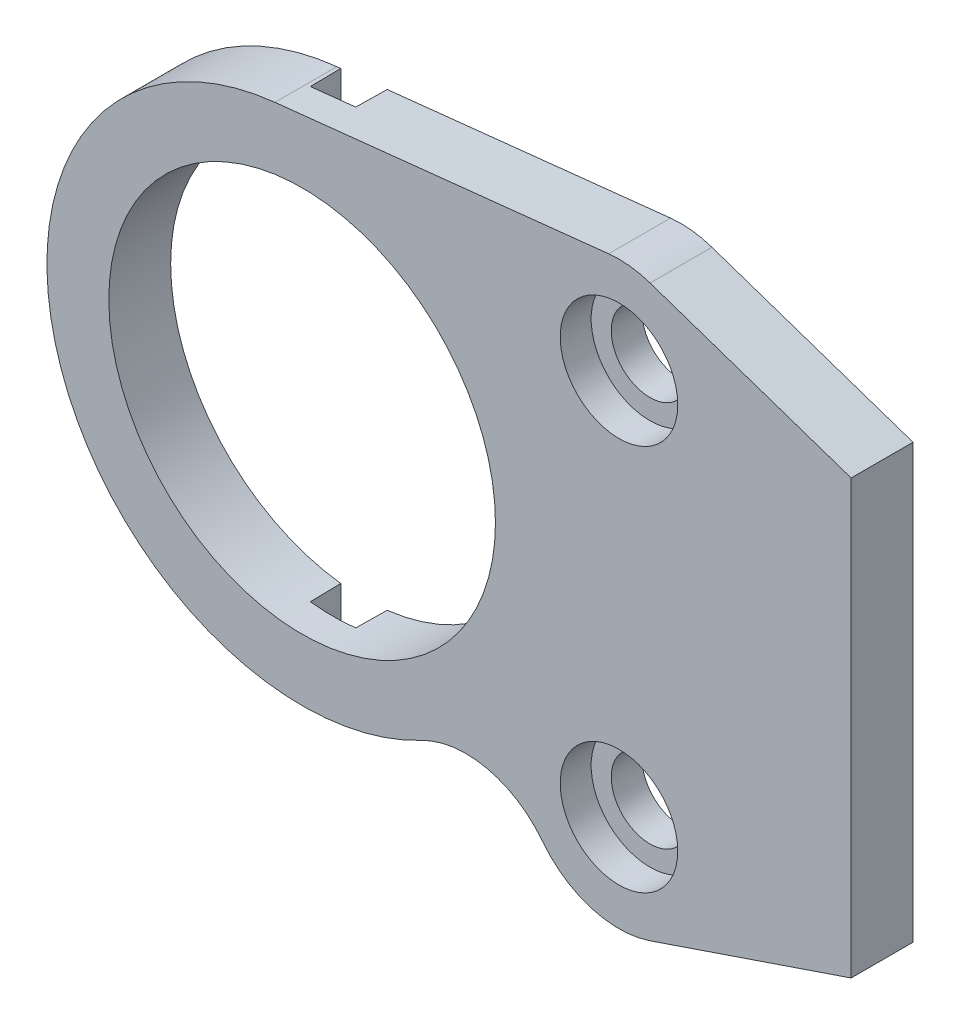
SolidWorks part; units mm, degrees
ref_plane "前视基准面" through (0, 0, 0) normal (0, 0, 1) x (1, 0, 0)
ref_plane "上视基准面" through (0, 0, 0) normal (0, 1, 0) x (1, 0, 0)
ref_plane "右视基准面" through (0, 0, 0) normal (1, 0, 0) x (0, 0, -1)
sketch "草图1" plane through (0, 0, 0) normal (0, 0, 1) x (1, 0, 0)
  line L0 (-3.5099, 32.8128) -> (39.6461, 37.4291)
  line L1 (44.9971, 36.8354) -> (71, 28)
  line L2 (71, 28) -> (71, -28)
  line L3 (71, -28) -> (44.9971, -36.8354)
  line L4 (55, 0) -> (-55, 0) construction
  line L5 (0, -55) -> (0, 55) construction
  circle A0 centre (0, 0) radius 33
  arc A1 (44.9971, -36.8354) -> (31.0781, -32.6347) centre (40.9756, -25) cw
  arc A2 (31.0781, -32.6347) -> (15.3617, -29.2064) centre (21.1806, -40.2695) ccw
  arc A3 (39.6461, 37.4291) -> (44.9971, 36.8354) centre (40.9756, 25) cw
  circle A4 centre (0, 0) radius 25
  point P19 (0, 0)
  dimension "D1" = 66
  dimension "D2" = 28
  dimension "D5" = 12.5
  dimension "D6" = 12.5
  dimension "D10" = 12.5
  dimension "D11" = 50
  dimension "D3" = 28
  dimension "D4" = 71
  dimension "D7" = 25
  dimension "D8" = 25
  dimension "D9" = 48
extrude "凸台-拉伸1" add sketch "草图1" along normal blind 8 contours A0 A4 | A3 L0 A0 A2 A1 L3 L2 L1
sketch "草图3" plane through (0, 0, 0) normal (0, 0, -1) x (-1, 0, 0)
  line L0 (0, 36.9433) -> (0, -38.1219)
  line L1 (0, 4.4) -> (0, -4.4) construction
extrude "切除-拉伸-薄壁1" cut sketch "草图3" against normal blind 4 draft 1 thin thin type mid plane wall 6
hole_wizard "孔1" positions "草图6" profile "草图7" legacy end condition up to next
sketch "草图6" plane through (0, 0, 8) normal (0, 0, 1) x (1, 0, 0)
  point P0 (40.9756, 25)
  point P3 (40.9756, -25)
sketch "草图7" plane through (40.9756, 25, 8) normal (1, 0, 0) x (0, -1, 0)
  line L0 (0, 0) -> (0, 8)
  line L1 (0, 8) -> (5, 8)
  line L2 (5, 8) -> (5, 4)
  line L3 (5, 4) -> (7.6, 4)
  line L4 (7.6, 4) -> (7.6, 0)
  line L5 (7.6, 0) -> (0, 0)
  line L6 (0, 110) -> (0, -10) construction
  dimension "直径" = 10
  dimension "深度" = 8
  dimension "柱坑直径" = 15.2
  dimension "柱坑深度" = 4
